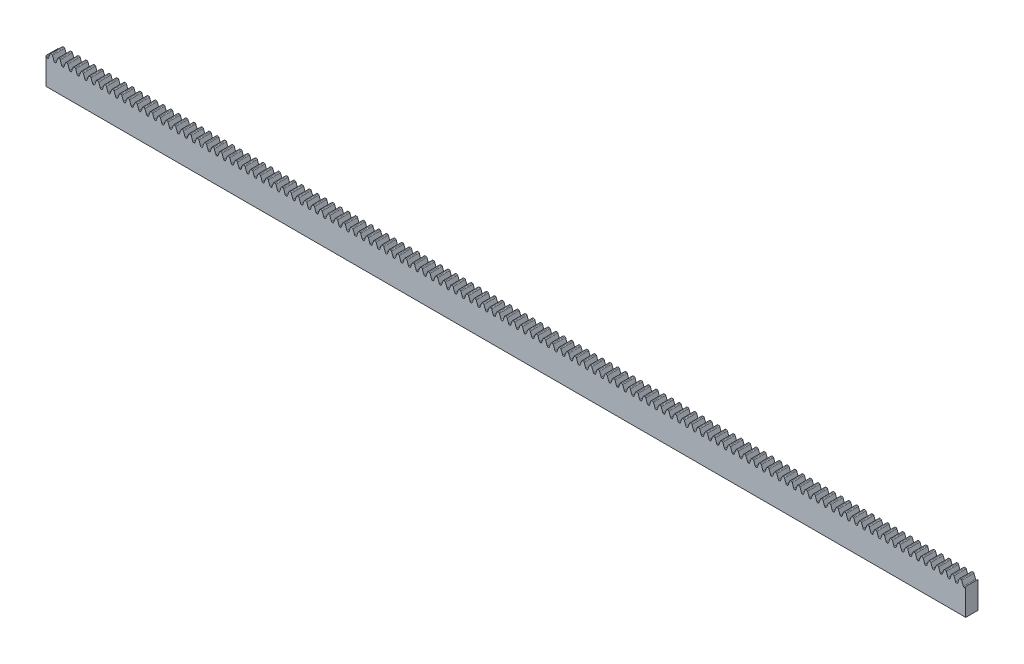
SolidWorks part; units mm, degrees
ref_plane "Front Plane" through (0, 0, 0) normal (0, 0, 1) x (1, 0, 0)
ref_plane "Top Plane" through (0, 0, 0) normal (0, 1, 0) x (1, 0, 0)
ref_plane "Right Plane" through (0, 0, 0) normal (1, 0, 0) x (0, 0, -1)
sketch "Sketch1" plane through (0, 0, 0) normal (0, 0, 1) x (1, 0, 0)
  line L0 (-150, 5) -> (-150, -5) construction
  line L1 (-150, -5) -> (150, -5) construction
  line L2 (150, -5) -> (150, 5) construction
  line L4 (0, 5) -> (0, -5) construction
  line L5 (-150, 4.2) -> (150, 4.2) construction
  line L6 (-148.6203, 5) -> (-147.946, 5) construction
  line L7 (-147.946, 5) -> (-147.2909, 3.2) construction
  line L8 (-148.6203, 5) -> (-149.2755, 3.2) construction
  line L9 (-149.2755, 3.2) -> (-147.2909, 3.2) construction
  line L10 (-148.2832, 5) -> (-148.2832, 3.2) construction
  line L11 (-150, 0) -> (-143.2566, 0) construction
  line L12 (150, 0) -> (143.2566, 0) construction
  point P15 (-145.7699, 5)
  point P16 (-59.5, -5)
  point P17 (-147.6549, 4.2)
  point P18 (-148.9115, 4.2)
  point P21 (-0.4, -5)
  dimension "Length" = 300
  dimension "Height" = 10
  dimension "Approximate Number of Teeth" = 119
  dimension "Pressure Angle" = 20
  dimension "Circular Pitch" = 2.5133
  dimension "Addendum" = 0.8
  dimension "Dedendum" = 1
  dimension "Circular Tooth Thickness" = 1.2566
  dimension "Module" = 0.8
  dimension "Rack Length" = 296.5663
  dimension "D1" = 5.0265
sketch "Sketch2" plane through (0, 0, 0) normal (1, 0, 0) x (0, 0, -1)
  line L0 (-2, 0) -> (2, 0) construction
  dimension "Face Width" = 4
sketch "Sketch3" plane through (0, 0, 0) normal (0, 0, 1) x (1, 0, 0)
  line L1 (-150, 5) -> (150, 5)
  line L2 (-150, 5) -> (-150, -5)
  line L3 (-150, -5) -> (150, -5)
  line L4 (150, 5) -> (150, -5)
extrude "Boss-Extrude1" add sketch "Sketch3" against normal up to vertex (2 mm away) and the other way up to vertex (2 mm away) up to point (0, 0, -2) other way up to point (0, 0, 2)
sketch "Sketch4" plane through (0, 0, 0) normal (0, 0, 1) x (1, 0, 0)
  line L0 (-148.2832, 5) -> (-145.7699, 5) construction
  line L9 (-147.0265, 5) -> (-147.0265, 3.2)
  line L10 (-147.0265, 3.2) -> (-147.2909, 3.2)
  line L11 (-147.2909, 3.2) -> (-147.946, 5)
  line L12 (-147.946, 5) -> (-147.0265, 5)
  line L13 (-148.6203, 5) -> (-149.2755, 3.2)
  line L14 (-149.2755, 3.2) -> (-149.5398, 3.2)
  line L15 (-149.5398, 3.2) -> (-149.5398, 5)
  line L16 (-149.5398, 5) -> (-148.6203, 5)
  line L17 (150, 5) -> (-150, 5) construction
  line L18 (-148.6203, 5) -> (-148.4324, 5)
  line L19 (-148.134, 5) -> (-147.946, 5)
  arc A0 (-149.4634, 3.2) -> (-149.2112, 3.3766) centre (-149.4634, 3.4684) ccw
  arc A1 (-147.3552, 3.3766) -> (-147.1029, 3.2) centre (-147.1029, 3.4684) ccw
  arc A2 (-148.6846, 4.8234) -> (-148.4324, 5) centre (-148.4324, 4.7316) cw
  arc A3 (-148.134, 5) -> (-147.8818, 4.8234) centre (-148.134, 4.7316) cw
  dimension "D1" = 0.2684
extrude "Cut-Extrude1" cut sketch "Sketch4" against normal through all both and the other way through all contours L14 A0 L13 L16 L15 | L13 A2 L18 | L19 A3 L11 | L11 A1 L10 L9 L12
pattern_linear "LPattern1" count 120 spacing 2.5133 along (1, 0, 0) count 2 spacing 2.5133 along (-1, 0, 0) of "Cut-Extrude1"
sketch "Drawing Refernce 1" plane through (0, 0, 2) normal (0, 0, 1) x (1, 0, 0)
  line L0 (-150, 0) -> (150, 0) construction
  point P6 (-135, 0)
  point P7 (-127.5, 0)
  point P8 (135, 0)
  dimension "D1" = 15
  dimension "D2" = 22.5
  dimension "D3" = 15
equation "\"Diametral Pitch\"= 1 / \"Module\""
equation "\"Pressure Angle\"=20"
equation "\"Dedendum\"= 1.25 / \"Diametral Pitch\""
equation "\"Addendum\"= 1 / \"Diametral Pitch\""
equation "\"WorkingDepth\"= 2 / \"Diametral Pitch\""
equation "\"WholeDepth\"= 2.25 / \"Diametral Pitch\""
equation "\"Clearance\"= 0.25 / \"Diametral Pitch\""
equation "\"ToothThickness\"= ( pi / 2 ) / \"Diametral Pitch\""
equation "\"CircularPitch\"= pi / \"Diametral Pitch\""
equation "\"Fillet\"= \"Clearance\" * cos ( \"Pressure Angle\" ) * tan ( ( 90 + \"Pressure Angle\" ) / 2 )"
equation "\"Module\"= 0.8"
equation "\"Addendum@Sketch1\"=\"Addendum\""
equation "\"Pressure Angle@Sketch1\"=\"Pressure Angle\""
equation "\"Dedendum@Sketch1\"=\"Dedendum\""
equation "\"Circular Pitch@Sketch1\"=\"CircularPitch\""
equation "\"Circular Tooth Thickness@Sketch1\"=\"ToothThickness\""
equation "\"Module@Sketch1\"=\"Module\""
equation "\"Approximate Number of Teeth@Sketch1\" = int ( \"Length@Sketch1\" /  ( 2 * \"Circular Tooth Thickness@Sketch1\" )  ) "
equation "\"Rack Length@Sketch1\" = \"Circular Pitch@Sketch1\" *  ( \"Approximate Number of Teeth@Sketch1\" - 1 ) "
equation "\"D3@LPattern1\"=\"CircularPitch\""
equation "\"D1@LPattern1\"=\"Approximate Number of Teeth@Sketch1\"+1"
equation "\"D1@Sketch1\"=\"Circular Pitch@Sketch1\"*2"
equation "\"D1@Sketch4\"=\"Fillet\""
equation "\"D4@LPattern1\"=\"CircularPitch\""
equation "\"D2@Drawing Refernce 1\"=\"D1@Drawing Refernce 1\"*1.5"
equation "\"D3@Drawing Refernce 1\"=\"D1@Drawing Refernce 1\""
